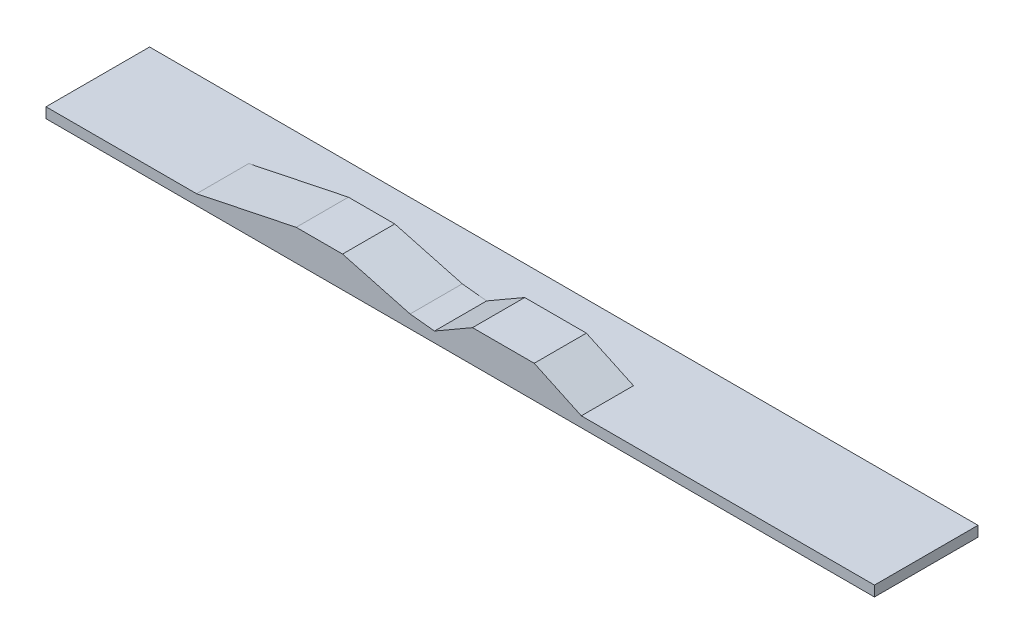
SolidWorks part; units mm, degrees
ref_plane "Front Plane" through (0, 0, 0) normal (0, 0, 1) x (1, 0, 0)
ref_plane "Top Plane" through (0, 0, 0) normal (0, 1, 0) x (1, 0, 0)
ref_plane "Right Plane" through (0, 0, 0) normal (1, 0, 0) x (0, 0, -1)
sketch "Sketch1" plane through (0, 0, 0) normal (0, 1, 0) x (1, 0, 0)
  line L1 (-4000, 500) -> (4000, 500)
  line L2 (-4000, 500) -> (-4000, -500)
  line L3 (-4000, -500) -> (4000, -500)
  line L4 (4000, 500) -> (4000, -500)
  line L5 (-4000, 500) -> (4000, -500) construction
  line L6 (-4000, -500) -> (4000, 500) construction
  point P0 (0, 0)
  dimension "D1" = 8000
  dimension "D2" = 1000
extrude "Boss-Extrude1" add sketch "Sketch1" along normal blind 100
sketch "Sketch2" plane through (0, 0, 500) normal (0, 0, 1) x (1, 0, 0)
  line L1 (-4000, 100) -> (4000, 100) construction
  line L5 (1169.3249, 100) -> (714.4187, 312.1262)
  line L6 (714.4187, 312.1262) -> (118.6209, 312.1262)
  line L7 (118.6209, 312.1262) -> (-248.7925, 100)
  line L8 (-248.7925, 100) -> (-483.8809, 125.2243)
  line L10 (-1136.1526, 300) -> (-1583.9791, 300)
  line L11 (-1583.9791, 300) -> (-2545.9769, 100)
  line L12 (-2545.9769, 100) -> (-2545.9769, 0)
  line L13 (-4000, 0) -> (4000, 0) construction
  line L14 (-2545.9769, 0) -> (2172.7881, 0)
  line L15 (2172.7881, 0) -> (2172.7881, 100)
  line L22 (1169.3249, 100) -> (2172.7881, 100)
  line L23 (-1136.1526, 300) -> (-483.8809, 125.2243)
  dimension "D1" = 15
  dimension "D2" = 25
  dimension "D3" = 200
  dimension "D4" = 30
extrude "Boss-Extrude2" add sketch "Sketch2" against normal blind 504
